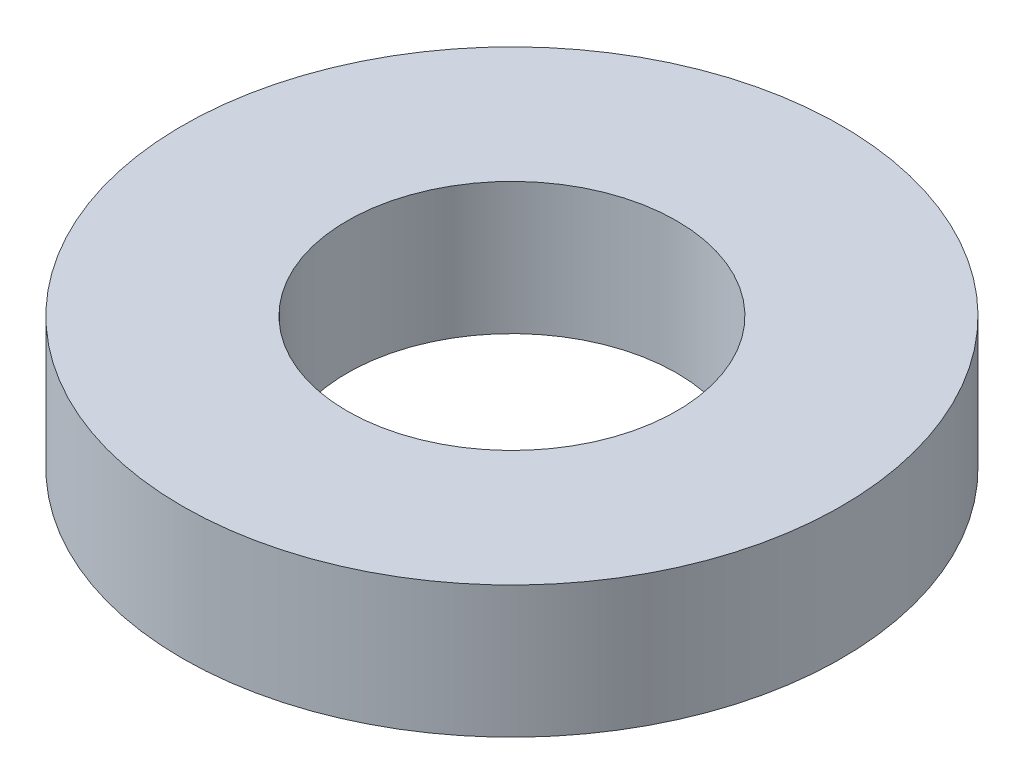
SolidWorks part; units mm, degrees
material "AISI 304"
ref_plane "前视基准面" through (0, 0, 0) normal (0, 0, 1) x (1, 0, 0)
ref_plane "上视基准面" through (0, 0, 0) normal (0, 1, 0) x (1, 0, 0)
ref_plane "右视基准面" through (0, 0, 0) normal (1, 0, 0) x (0, 0, -1)
other "Configuration Table"
sketch "草图1" plane through (0, 0, 0) normal (0, 1, 0) x (1, 0, 0)
  circle A0 centre (0, 0) radius 5
  circle A1 centre (0, 0) radius 2.5
  dimension "D1" = 5
  dimension "D2" = 10
extrude "凸台-拉伸1" add sketch "草图1" along normal blind 2
